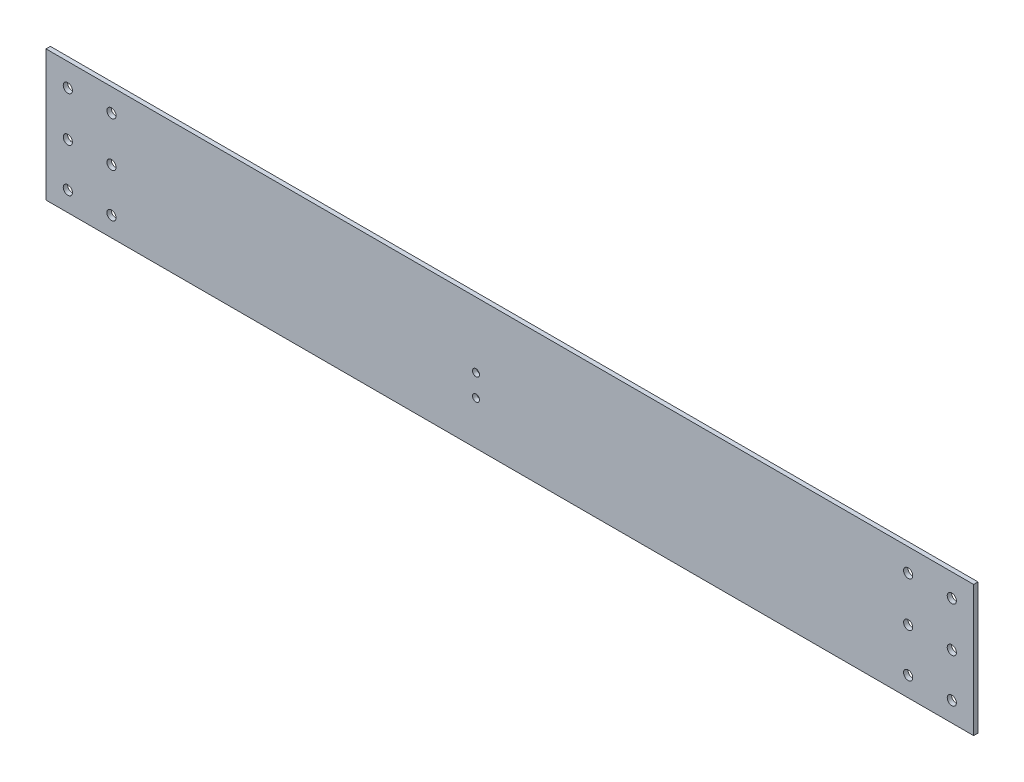
SolidWorks part; units mm, degrees
material "Thornel Mat VMA"
ref_plane "前视基准面" through (0, 0, 0) normal (0, 0, 1) x (1, 0, 0)
ref_plane "上视基准面" through (0, 0, 0) normal (0, 1, 0) x (1, 0, 0)
ref_plane "右视基准面" through (0, 0, 0) normal (1, 0, 0) x (0, 0, -1)
other "Configuration Table"
sketch "草图1" plane through (0, 0, 0) normal (0, 0, 1) x (1, 0, 0)
  line L1 (-212.5, 30) -> (212.5, 30)
  line L2 (-212.5, 30) -> (-212.5, -30)
  line L3 (-212.5, -30) -> (212.5, -30)
  line L4 (212.5, 30) -> (212.5, -30)
  line L5 (0, -30) -> (0, 30) construction
  line L6 (-212.5, 0) -> (212.5, 0) construction
  point P0 (0, 0)
  dimension "D1" = 425
  dimension "D2" = 60
extrude "凸台-拉伸1" add sketch "草图1" along normal blind 2
sketch "草图2" plane through (0, 0, 0) normal (0, 0, -1) x (-1, 0, 0)
  line L0 (15.5, 30) -> (15.5, -30) construction
  line L1 (-212.5, 30) -> (212.5, 30) construction
  line L2 (212.5, -30) -> (-212.5, -30) construction
  circle A0 centre (202.5, -21) radius 2.1 construction
  circle A1 centre (182.5, -21) radius 2.1 construction
  circle A2 centre (202.5, 19.5) radius 2.1 construction
  circle A3 centre (202.5, -1) radius 2.1 construction
  circle A4 centre (182.5, -1) radius 2.1 construction
  circle A5 centre (182.5, 19.5) radius 2.1 construction
  circle A6 centre (202.5, -21) radius 2.1
  circle A7 centre (182.5, -21) radius 2.1
  circle A8 centre (202.5, 19.5) radius 2.1
  circle A9 centre (202.5, -1) radius 2.1
  circle A10 centre (182.5, -1) radius 2.1
  circle A11 centre (182.5, 19.5) radius 2.1
  circle A12 centre (-182.5, -21) radius 2.1 construction
  circle A13 centre (-202.5, -21) radius 2.1 construction
  circle A14 centre (-182.5, -1) radius 2.1 construction
  circle A15 centre (-202.5, -1) radius 2.1 construction
  circle A16 centre (-202.5, 19.5) radius 2.1 construction
  circle A17 centre (-182.5, 19.5) radius 2.1 construction
  circle A20 centre (-182.5, -21) radius 2.1
  circle A21 centre (-202.5, -21) radius 2.1
  circle A22 centre (-182.5, -1) radius 2.1
  circle A23 centre (-202.5, -1) radius 2.1
  circle A24 centre (-202.5, 19.5) radius 2.1
  circle A25 centre (-182.5, 19.5) radius 2.1
  circle A28 centre (15.5, -10) radius 1.6
  circle A29 centre (15.5, 0) radius 1.6
  dimension "D4" = 3.2
  dimension "D5" = 3.2
  dimension "D1" = 15.5
  dimension "D2" = 20
  dimension "D3" = 10
extrude "切除-拉伸1" cut sketch "草图2" against normal through all
